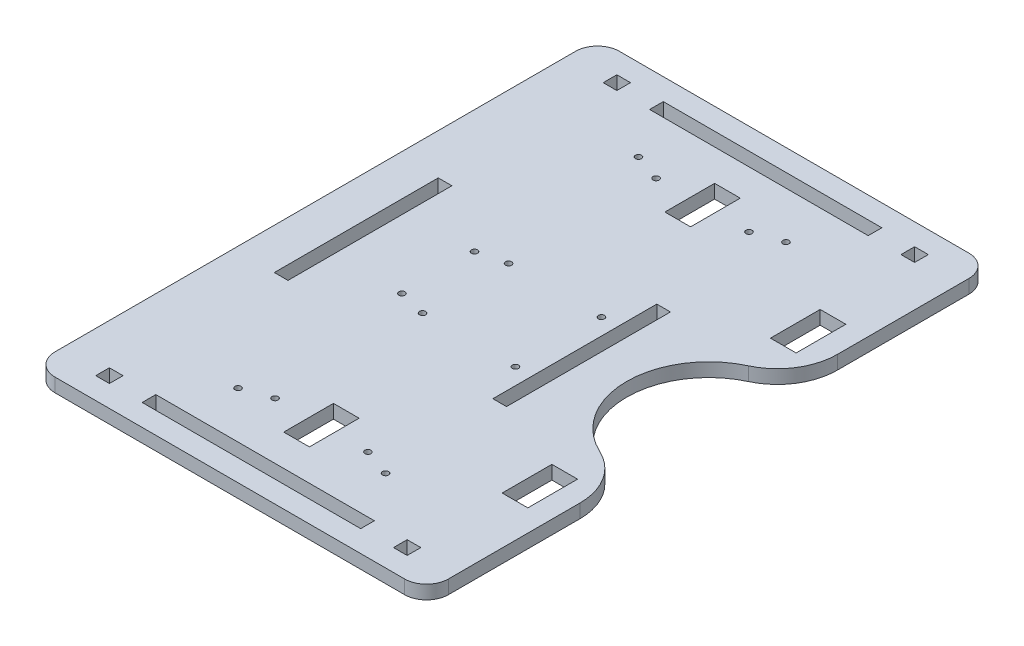
SolidWorks part; units mm, degrees
ref_plane "Front Plane" through (0, 0, 0) normal (0, 0, 1) x (1, 0, 0)
ref_plane "Top Plane" through (0, 0, 0) normal (0, 1, 0) x (1, 0, 0)
ref_plane "Right Plane" through (0, 0, 0) normal (1, 0, 0) x (0, 0, -1)
sketch "Sketch3" plane through (0, 0, 0) normal (0, 1, 0) x (1, 0, 0)
  line L4 (182.88, 0) -> (0, 0)
  line L5 (91.44, 262.3393) -> (91.44, 0) construction
  line L6 (19.05, 16.3877) -> (25.4, 16.3877)
  line L7 (19.05, 16.3877) -> (19.05, 10.0377)
  line L8 (19.05, 10.0377) -> (25.4, 10.0377)
  line L9 (25.4, 16.3877) -> (25.4, 10.0377)
  line L10 (163.83, 10.0377) -> (157.48, 10.0377)
  line L11 (157.48, 16.3877) -> (157.48, 10.0377)
  line L12 (163.83, 16.3877) -> (157.48, 16.3877)
  line L13 (163.83, 16.3877) -> (163.83, 10.0377)
  line L14 (0, 0) -> (0, 262.3393)
  line L15 (0, 262.3393) -> (182.88, 262.3393)
  line L16 (182.88, 262.3393) -> (182.88, 169.2696)
  line L17 (0, 131.1696) -> (152.4, 131.1696) construction
  line L18 (163.83, 245.9515) -> (163.83, 252.3015)
  line L19 (163.83, 245.9515) -> (157.48, 245.9515)
  line L20 (157.48, 245.9515) -> (157.48, 252.3015)
  line L21 (163.83, 252.3015) -> (157.48, 252.3015)
  line L22 (19.05, 252.3015) -> (25.4, 252.3015)
  line L23 (25.4, 245.9515) -> (25.4, 252.3015)
  line L24 (19.05, 245.9515) -> (25.4, 245.9515)
  line L25 (19.05, 245.9515) -> (19.05, 252.3015)
  line L26 (182.88, 93.0696) -> (182.88, 0)
  line L27 (172.72, 205.0836) -> (160.782, 205.0836)
  line L28 (172.72, 80.3696) -> (160.782, 80.3696)
  line L29 (172.72, 80.3696) -> (172.72, 57.2556)
  line L30 (172.72, 57.2556) -> (160.782, 57.2556)
  line L31 (160.782, 80.3696) -> (160.782, 57.2556)
  line L32 (172.72, 181.9696) -> (160.782, 181.9696)
  line L33 (172.72, 181.9696) -> (172.72, 205.0836)
  line L34 (160.782, 181.9696) -> (160.782, 205.0836)
  line L35 (40.64, 252.3015) -> (142.24, 252.3015)
  line L36 (40.64, 16.3877) -> (142.24, 16.3877)
  line L37 (40.64, 16.3877) -> (40.64, 10.0377)
  line L38 (40.64, 10.0377) -> (142.24, 10.0377)
  line L39 (142.24, 16.3877) -> (142.24, 10.0377)
  line L40 (142.24, 245.9515) -> (142.24, 252.3015)
  line L41 (40.64, 245.9515) -> (142.24, 245.9515)
  line L42 (40.64, 245.9515) -> (40.64, 252.3015)
  line L43 (127, 93.0696) -> (120.65, 93.0696)
  line L48 (120.65, 169.2696) -> (120.65, 93.0696)
  line L49 (127, 169.2696) -> (120.65, 169.2696)
  line L50 (127, 169.2696) -> (127, 93.0696)
  line L51 (25.4, 93.0696) -> (19.05, 93.0696)
  line L52 (19.05, 169.2696) -> (19.05, 93.0696)
  line L53 (25.4, 169.2696) -> (19.05, 169.2696)
  line L54 (25.4, 169.2696) -> (25.4, 93.0696)
  line L55 (97.409, 54.1311) -> (85.471, 54.1311)
  line L56 (97.409, 54.1311) -> (97.409, 31.0171)
  line L57 (97.409, 31.0171) -> (85.471, 31.0171)
  line L58 (85.471, 54.1311) -> (85.471, 31.0171)
  line L59 (97.409, 208.2081) -> (97.409, 231.3221)
  line L60 (97.409, 231.3221) -> (85.471, 231.3221)
  line L61 (85.471, 208.2081) -> (85.471, 231.3221)
  line L62 (97.409, 208.2081) -> (85.471, 208.2081)
  circle A6 centre (57.15, 38.1) radius 1.4224
  circle A7 centre (57.15, 114.3) radius 1.4224
  circle A9 centre (125.73, 38.1) radius 1.4224
  circle A10 centre (69.85, 151.1577) radius 1.4224
  circle A11 centre (69.85, 219.7377) radius 1.4224
  circle A12 centre (113.03, 151.1577) radius 1.4224
  circle A13 centre (113.03, 219.7377) radius 1.4224
  circle A14 centre (113.03, 42.6016) radius 1.4224
  circle A15 centre (113.03, 111.1816) radius 1.4224
  circle A16 centre (69.85, 111.1816) radius 1.4224
  circle A17 centre (69.85, 42.6016) radius 1.4224
  circle A19 centre (125.73, 224.2393) radius 1.4224
  circle A20 centre (57.15, 224.2393) radius 1.4224
  circle A21 centre (57.15, 148.0393) radius 1.4224
  arc A22 (182.88, 169.2696) -> (182.88, 93.0696) centre (182.88, 131.1696) ccw
  dimension "D2" = 19.05
  dimension "D3" = 0
  dimension "D10" = 38.1
  dimension "D13" = 68.58
  dimension "D8" = 23.114
  dimension "D4" = 19.05
  dimension "D5" = 182.88
  dimension "D6" = 6.35
  dimension "D7" = 6.35
  dimension "D9" = 11.938
  dimension "D11" = 85.471
  dimension "D12" = 68.58
  dimension "D14" = 43.18
  dimension "D15" = 50.8
  dimension "D16" = 10.16
  dimension "D17" = 101.6
  dimension "D18" = 6.35
  dimension "D19" = 50.8
  dimension "D20" = 55.88
  dimension "D21" = 38.1
  dimension "D22" = 6.35
  dimension "D23" = 6.35
  dimension "D24" = 19.05
extrude "Boss-Extrude1" add sketch "Sketch3" along normal blind 6.35
fillet "Fillet1" radius 10.16 4 edges at (0, 3.175, 0) (0, 3.175, -262.3393) (182.88, 3.175, -262.3393) (182.88, 3.175, 0)
fillet "Fillet2" radius 27.94 2 edges at (182.88, 3.175, -169.2696) (182.88, 3.175, -93.0696)
